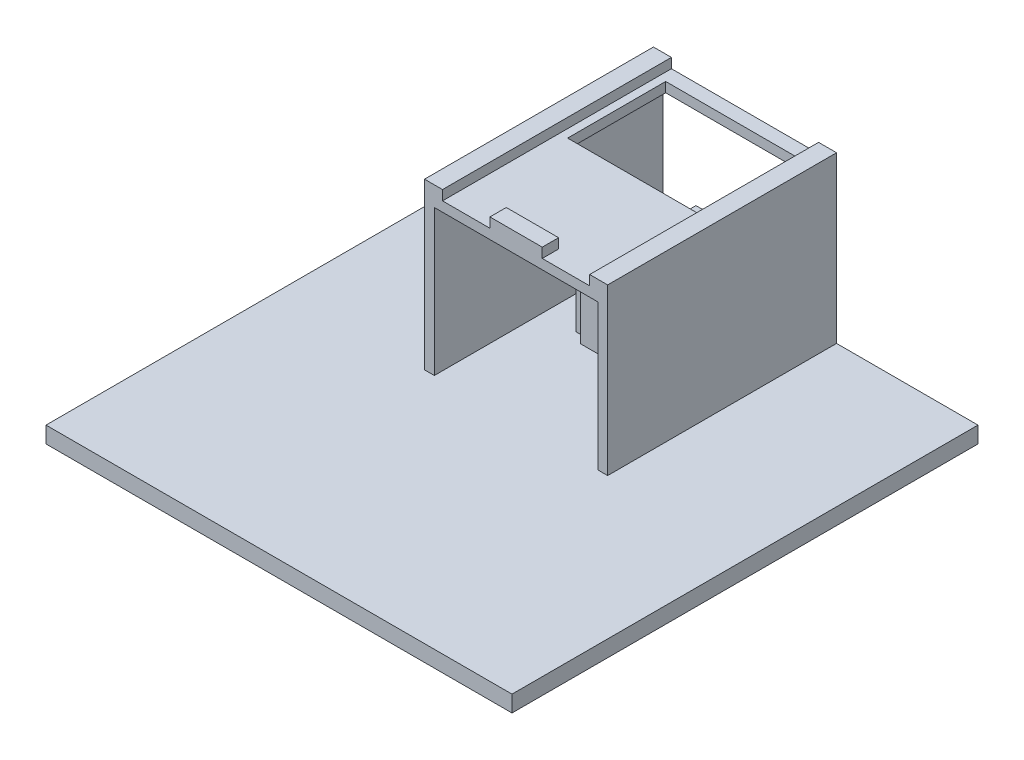
SolidWorks part; units mm, degrees
ref_plane "Front Plane" through (0, 0, 0) normal (0, 0, 1) x (1, 0, 0)
ref_plane "Top Plane" through (0, 0, 0) normal (0, 1, 0) x (1, 0, 0)
ref_plane "Right Plane" through (0, 0, 0) normal (1, 0, 0) x (0, 0, -1)
sketch "Sketch1" plane through (0, 0, 0) normal (0, 0, 1) x (1, 0, 0)
  line L3 (9, -3.6) -> (9, -21.4)
  line L4 (10.2, -21.4) -> (9, -21.4)
  line L5 (-4.2, -1.2) -> (-4.2, -2.4)
  line L6 (-4.2, -2.4) -> (-10, -2.4)
  line L7 (-10, -2.4) -> (-10, -1.2)
  line L8 (-10, -1.2) -> (-12.2, -1.2)
  line L9 (-4.2, -1.2) -> (2.2, -1.2)
  line L10 (-12.2, -1.2) -> (-12.2, -21.4)
  line L11 (-12.2, -21.4) -> (-11, -21.4)
  line L13 (9, -3.6) -> (-11, -3.6)
  line L14 (-11, -3.6) -> (-11, -21.4)
  line L15 (10.2, -1.2) -> (10.2, -21.4)
  line L16 (8, -1.2) -> (10.2, -1.2)
  line L17 (8, -2.4) -> (8, -1.2)
  line L18 (2.2, -2.4) -> (8, -2.4)
  line L19 (2.2, -1.2) -> (2.2, -2.4)
extrude "Boss-Extrude2" add sketch "Sketch1" along normal blind 28 contours L3 L4 L15 L16 L17 L18 L19 L9 L5 L6 L7 L8 L10 L11 L14 L13
sketch "Sketch4" plane through (0, -1.2, 0) normal (0, 1, 0) x (1, 0, 0)
  line L0 (-4.2, 0) -> (2.2, 0)
  line L1 (2.2, 0) -> (2.2, -26)
  line L2 (-4.2, -26) -> (2.2, -26)
  line L3 (-4.2, -26) -> (-4.2, 0)
  line L4 (-4.2, -28) -> (-4.2, 0) construction
extrude "Cut-Extrude2" cut sketch "Sketch4" against normal blind 1.2
sketch "Sketch5" plane through (0, -2.4, 0) normal (0, 1, 0) x (1, 0, 0)
  line L3 (-9, -1.7) -> (7, -1.7)
  line L4 (7, -1.7) -> (7, -13.7)
  line L5 (-9, -1.7) -> (-9, -13.7)
  line L6 (-9, -13.7) -> (7, -13.7)
extrude "Cut-Extrude3" cut sketch "Sketch5" against normal blind 1.2
sketch "Sketch6" plane through (0, 0, 13.7) normal (0, 0, -1) x (-1, 0, 0)
  line L1 (9, -3.6) -> (-7, -3.6) construction
  line L3 (-3.4, -3.6) -> (5.4, -3.6)
  line L4 (-3.4, -3.6) -> (-3.4, -21.4)
  line L5 (-3.4, -21.4) -> (5.4, -21.4)
  line L6 (5.4, -21.4) -> (5.4, -3.6)
extrude "Boss-Extrude3" add sketch "Sketch6" against normal blind 2
sketch "Sketch7" plane through (0, 0, 15.7) normal (0, 0, 1) x (1, 0, 0)
  line L1 (-7, -21.4) -> (-7, -15.4)
  line L2 (-7, -15.4) -> (5, -15.4)
  line L3 (5, -15.4) -> (5, -21.4)
  line L4 (5, -21.4) -> (-7, -21.4)
extrude "Boss-Extrude4" add sketch "Sketch7" against normal blind 15.7
sketch "Sketch8" plane through (0, 0, 15.7) normal (0, 0, 1) x (1, 0, 0)
  line L0 (-7, -15.4) -> (-5.4, -15.4)
  line L1 (-5.4, -15.4) -> (-7, -15.4) construction
  line L2 (-5.4, -15.4) -> (-5.4, -21.4)
  line L3 (5, -21.4) -> (-7, -21.4) construction
  line L4 (-5.4, -21.4) -> (-7, -21.4)
  line L5 (-7, -21.4) -> (-7, -15.4)
  line L6 (3.4, -15.4) -> (5, -15.4)
  line L7 (5, -15.4) -> (5, -21.4)
  line L8 (5, -21.4) -> (3.4, -21.4)
  line L9 (3.4, -21.4) -> (3.4, -15.4)
extrude "Cut-Extrude4" cut sketch "Sketch8" against normal blind 1
sketch "Sketch9" plane through (0, 0, 0) normal (0, 0, -1) x (-1, 0, 0)
  line L9 (1, -21.4) -> (29.5, -21.4)
  line L10 (7, -21.4) -> (-5, -21.4) construction
  line L11 (1, -21.4) -> (-27.5, -21.4)
  line L12 (-27.5, -21.4) -> (-27.5, -23.4)
  line L13 (-27.5, -23.4) -> (29.5, -23.4)
  line L14 (29.5, -23.4) -> (29.5, -21.4)
extrude "Boss-Extrude10" add sketch "Sketch9" against normal blind 57
